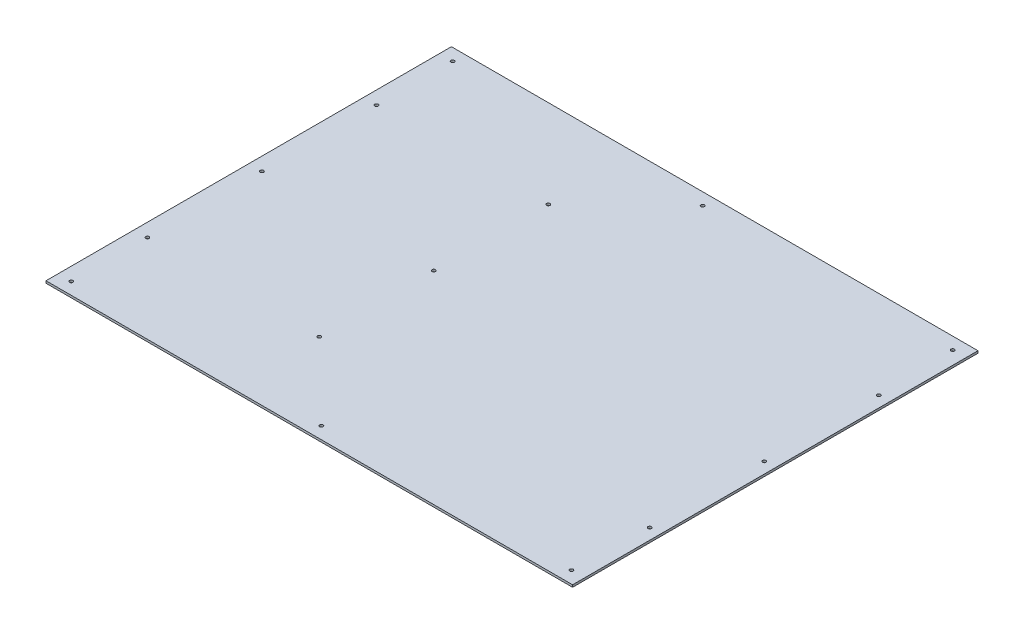
SolidWorks part; units mm, degrees
material "ABS PC"
ref_plane "Front Plane" through (0, 0, 0) normal (0, 0, 1) x (1, 0, 0)
ref_plane "Top Plane" through (0, 0, 0) normal (0, 1, 0) x (1, 0, 0)
ref_plane "Right Plane" through (0, 0, 0) normal (1, 0, 0) x (0, 0, -1)
sketch "Sketch1" plane through (0, 0, 0) normal (0, 1, 0) x (1, 0, 0)
  line L1 (0, 0) -> (758.825, 0)
  line L2 (0, 0) -> (0, 584.2)
  line L3 (0, 584.2) -> (758.825, 584.2)
  line L4 (758.825, 0) -> (758.825, 584.2)
  dimension "D1" = 758.825
  dimension "D2" = 584.2
extrude "Boss-Extrude1" add sketch "Sketch1" along normal blind 3.175
sketch "Sketch2" plane through (0, 3.175, 0) normal (0, 1, 0) x (1, 0, 0)
  line L4 (758.825, 584.2) -> (0, 584.2) construction
  line L5 (758.825, 0) -> (758.825, 584.2) construction
  line L6 (428.625, 317.5) -> (428.625, 190.5) construction
  line L7 (441.325, 203.2) -> (314.325, 203.2) construction
  line L8 (381, 317.5) -> (381, 263.1528) construction
  line L9 (381, 290.3264) -> (441.325, 290.3264) construction
  line L10 (441.325, 290.3264) -> (314.325, 290.3264) construction
  line L11 (314.325, 290.3264) -> (314.325, 317.5) construction
  line L12 (314.325, 290.3264) -> (314.325, 190.5) construction
  line L13 (314.325, 317.5) -> (441.325, 317.5) construction
  line L14 (441.325, 317.5) -> (441.325, 190.5) construction
  line L15 (441.325, 190.5) -> (314.325, 190.5) construction
  line L16 (327.025, 317.5) -> (327.025, 190.5) construction
  line L17 (314.325, 304.8) -> (441.325, 304.8) construction
  dimension "D1" = 127
  dimension "D2" = 127
  dimension "D3" = 12.7
  dimension "D4" = 12.7
  dimension "D5" = 266.7
  dimension "D6" = 317.5
  dimension "D7" = 12.7
  dimension "D8" = 12.7
hole_wizard "#10 (0.1935) Diameter Hole2" positions "Sketch7" profile "Sketch6" hole size "#10" standard "ANSI Inch" end condition through all
sketch "Sketch7" plane through (0, 3.175, 0) normal (0, 1, 0) x (1, 0, 0)
  line L0 (758.825, 584.2) -> (0, 584.2) construction
  line L1 (0, 584.2) -> (0, 0) construction
  line L2 (0, 0) -> (758.825, 0) construction
  line L3 (758.825, 0) -> (758.825, 584.2) construction
  line L4 (0, 292.1) -> (758.825, 292.1) construction
  line L9 (19.05, 566.801) -> (19.05, 17.399) construction
  line L12 (0, 584.2) -> (0, 0) construction
  line L13 (758.825, 584.2) -> (0, 584.2) construction
  line L14 (0, 0) -> (758.825, 0) construction
  line L15 (379.4125, 584.2) -> (379.4125, 0) construction
  point P0 (19.05, 566.801)
  point P12 (739.775, 566.801)
  point P14 (19.05, 17.399)
  point P16 (739.775, 17.399)
  point P39 (379.4125, 566.801)
  point P41 (19.05, 292.1)
  point P43 (379.4125, 17.399)
  point P45 (742.95, 292.1)
  point P48 (19.05, 457.2)
  point P50 (19.05, 127)
  point P52 (742.95, 127)
  point P54 (742.95, 457.2)
  dimension "D1" = 17.399
  dimension "D2" = 19.05
  dimension "D3" = 17.399
  dimension "D4" = 17.399
  dimension "D5" = 19.05
  dimension "D6" = 17.399
  dimension "D7" = 17.399
  dimension "D8" = 19.05
  dimension "D9" = 165.1
  dimension "D10" = 165.1
  dimension "D11" = 165.1
  dimension "D12" = 165.1
  dimension "D13" = 17.399
sketch "Sketch6" plane through (19.05, 3.175, -566.801) normal (1, 0, 0) x (0, 0, 1)
  line L0 (0, 0) -> (0, 3.175)
  line L1 (0, 3.175) -> (2.4574, 3.175)
  line L2 (2.4574, 3.175) -> (2.4574, 0)
  line L5 (2.4574, 0) -> (0, 0)
  line L11 (0, -6.35) -> (0, 107.95) construction
  dimension "Thru Hole Dia." = 4.9149
  dimension "Thru Hole Depth" = 3.175
hole_wizard "#10 (0.1935) Diameter Hole3" positions "Sketch9" profile "Sketch10" hole size "#10" standard "ANSI Inch" end condition through all
sketch "Sketch9" plane through (0, 3.175, 0) normal (0, 1, 0) x (1, 0, 0)
  line L0 (0, 584.2) -> (0, 0) construction
  line L1 (758.825, 584.2) -> (0, 584.2) construction
  point P0 (266.7, 292.1)
  point P2 (266.7, 127)
  point P4 (266.7, 457.2)
  dimension "D1" = 266.7
  dimension "D2" = 266.7
  dimension "D3" = 266.7
  dimension "D4" = 165.1
  dimension "D5" = 165.1
  dimension "D6" = 127
sketch "Sketch10" plane through (266.7, 3.175, -292.1) normal (1, 0, 0) x (0, 0, 1)
  line L0 (0, 0) -> (0, 3.175)
  line L1 (0, 3.175) -> (2.4574, 3.175)
  line L2 (2.4574, 3.175) -> (2.4574, 0)
  line L5 (2.4574, 0) -> (0, 0)
  line L11 (0, -6.35) -> (0, 107.95) construction
  dimension "Thru Hole Dia." = 4.9149
  dimension "Thru Hole Depth" = 3.175
